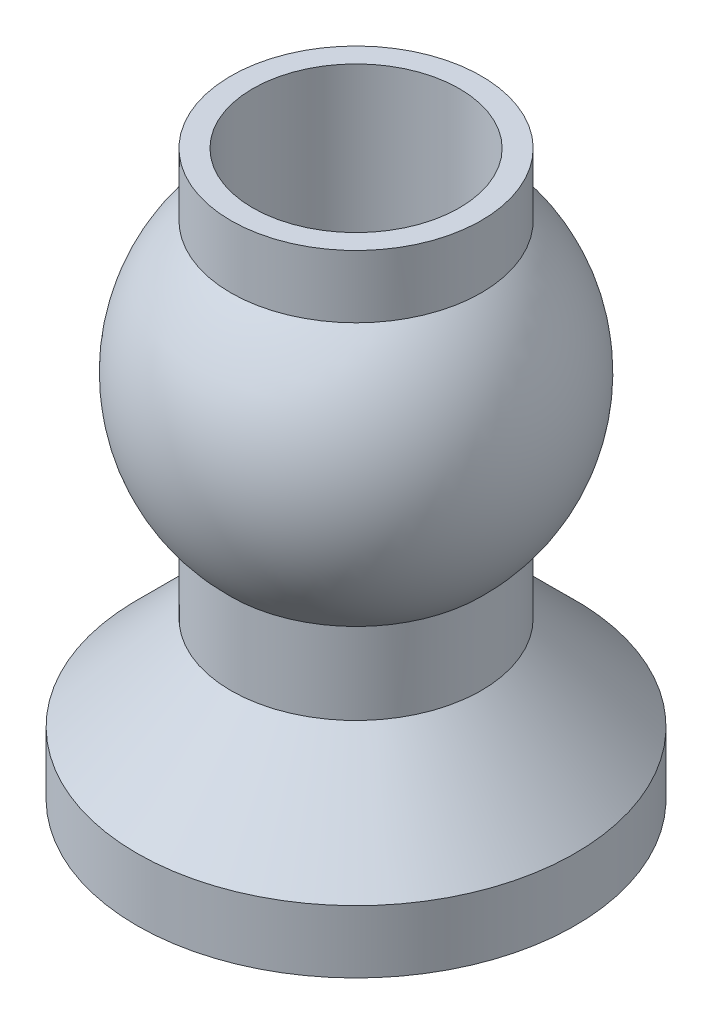
SolidWorks part; units mm, degrees
ref_plane "Front Plane" through (0, 0, 0) normal (0, 0, 1) x (1, 0, 0)
ref_plane "Top Plane" through (0, 0, 0) normal (0, 1, 0) x (1, 0, 0)
ref_plane "Right Plane" through (0, 0, 0) normal (1, 0, 0) x (0, 0, -1)
sketch "Sketch1" plane through (0, 0, 0) normal (0, 0, 1) x (1, 0, 0)
  line L0 (0, 9.8166) -> (0, -11.1633) construction
  line L1 (0, 4.5) -> (0, -4.5)
  line L2 (0, -4.5) -> (3.5, -4.5)
  line L3 (3.5, -4.5) -> (3.5, -3.5)
  line L4 (3.5, -3.5) -> (2, -2)
  line L5 (2, -2) -> (2, -0.7)
  line L6 (2, 4.5) -> (0, 4.5)
  line L7 (2, 3.5) -> (2, 4.5)
  arc A0 (2, 3.5) -> (2, -0.7) centre (0, 1.4) cw
  point P12 (2, 3.5)
  dimension "D6" = 2.9
  dimension "D1" = 9
  dimension "D2" = 1
  dimension "D3" = 6.5
  dimension "D4" = 3.5
  dimension "D5" = 2
  dimension "D7" = 1
revolve "Revolve1" add sketch "Sketch1" angle 360 about L0
sketch "Sketch2" plane through (0, 4.5, 0) normal (0, 1, 0) x (1, 0, 0)
  circle A0 centre (0, 0) radius 1.65
  dimension "D1" = 3.3
extrude "Cut-Extrude1" cut sketch "Sketch2" against normal blind 12.5
sketch "Sketch3" plane through (0, 0, 0) normal (1, 0, 0) x (0, 0, -1)
  line L3 (0, 3.15) -> (0, -10.6911) construction
